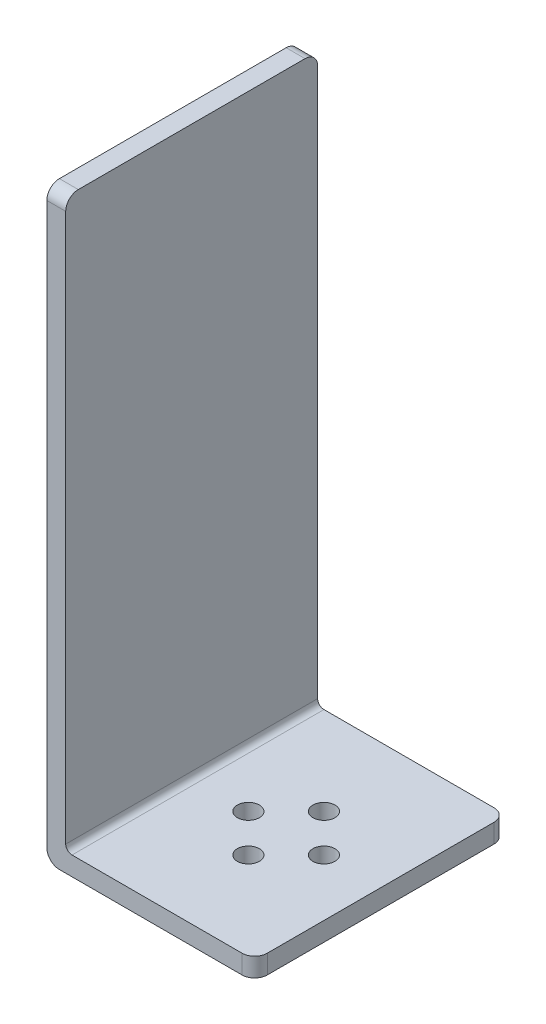
SolidWorks part; units mm, degrees
ref_plane "Plan de face" through (0, 0, 0) normal (0, 0, 1) x (1, 0, 0)
ref_plane "Plan de dessus" through (0, 0, 0) normal (0, 1, 0) x (1, 0, 0)
ref_plane "Plan de droite" through (0, 0, 0) normal (1, 0, 0) x (0, 0, -1)
sketch "Esquisse1" plane through (0, 0, 0) normal (0, 0, 1) x (1, 0, 0)
  line L0 (0, 0) -> (0, 90)
  line L1 (0, 0) -> (30, 0)
  dimension "D1" = 30
  dimension "D2" = 90
extrude "Extru.-Mince1" add sketch "Esquisse1" along normal blind 40 thin thin type one direction wall 3
fillet "Congé1" radius 1 1 edges at (0, 0, 20)
fillet "Congé2" radius 2 1 edges at (-3, -3, 20)
fillet "Congé3" radius 2 1 edges at (-1.5, 90, 40)
fillet "Congé4" radius 2 1 edges at (-1.5, 90, 0)
fillet "Congé5" radius 2 1 edges at (30, -1.5, 40)
fillet "Congé6" radius 2 1 edges at (30, -1.5, 0)
sketch "Esquisse3" plane through (0, 0, 0) normal (0, 1, 0) x (1, 0, 0)
  line L0 (48.1148, -20) -> (80.235, -20) construction
  line L1 (15, -5.0415) -> (15, -47.0776) construction
  line L2 (30, -38) -> (30, -2) construction
  line L3 (1, 0) -> (28, 0) construction
  circle A0 centre (15, -14) radius 1.75
  circle A1 centre (15, -26) radius 1.75
  circle A2 centre (21, -20) radius 1.75
  circle A3 centre (9, -20) radius 1.75
  dimension "D5" = 3.5
  dimension "D6" = 3.5
  dimension "D7" = 3.5
  dimension "D8" = 3.5
  dimension "D1" = 6
  dimension "D2" = 6
  dimension "D3" = 6
  dimension "D4" = 6
  dimension "D10" = 15
  dimension "D11" = 20
extrude "Enlèv. mat.-Extru.2" cut sketch "Esquisse3" against normal blind 10
